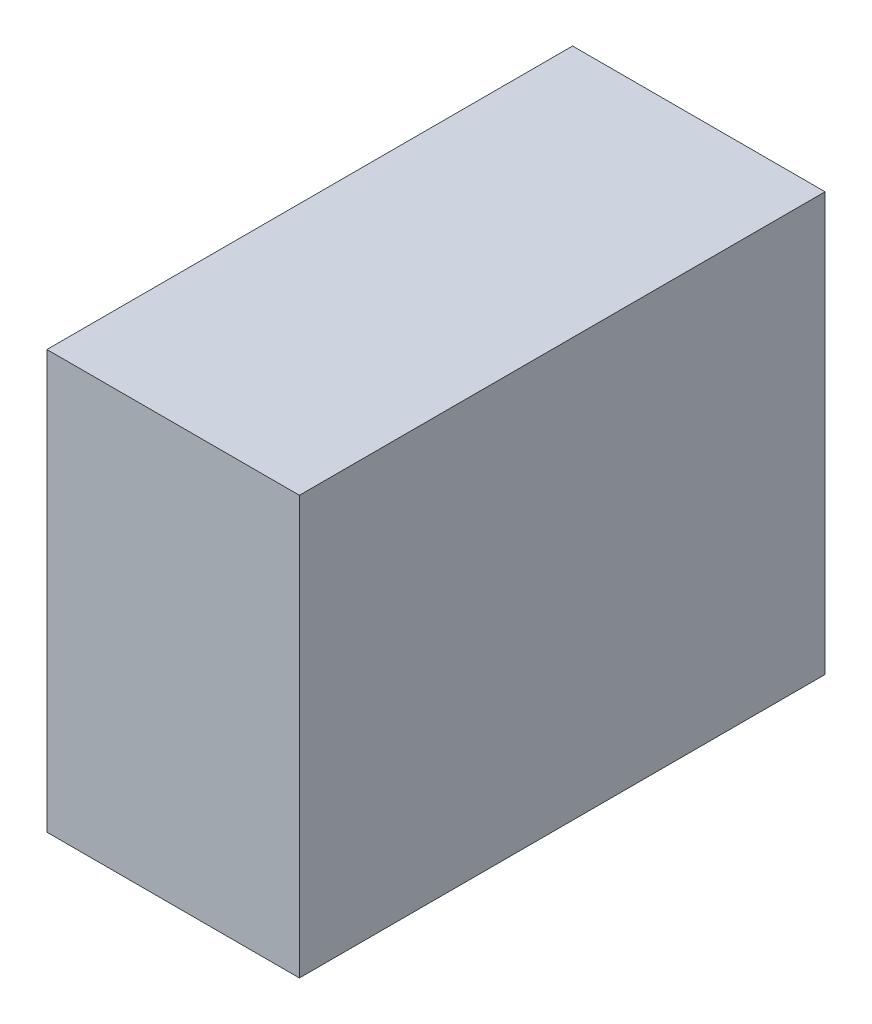
SolidWorks part; units mm, degrees
ref_plane "正面" through (0, 0, 0) normal (1, 0, 0) x (0, 1, 0)
ref_plane "平面" through (0, 0, 0) normal (0, 0, 1) x (0, 1, 0)
ref_plane "右側面" through (0, 0, 0) normal (0, 1, 0) x (-1, 0, 0)
sketch "ｽｹｯﾁ1" plane through (0, 0, 0) normal (0, 0, 1) x (0, 1, 0)
  line L1 (-2.525, 3.05) -> (2.525, 3.05)
  line L2 (-2.525, 3.05) -> (-2.525, 0)
  line L3 (-2.525, 0) -> (2.525, 0)
  line L4 (2.525, 3.05) -> (2.525, 0)
  point P4 (0, 0)
  dimension "D1" = 5.05
  dimension "D2" = 3.05
extrude "ﾎﾞｽ - 押し出し1" add sketch "ｽｹｯﾁ1" along normal blind 6.35
